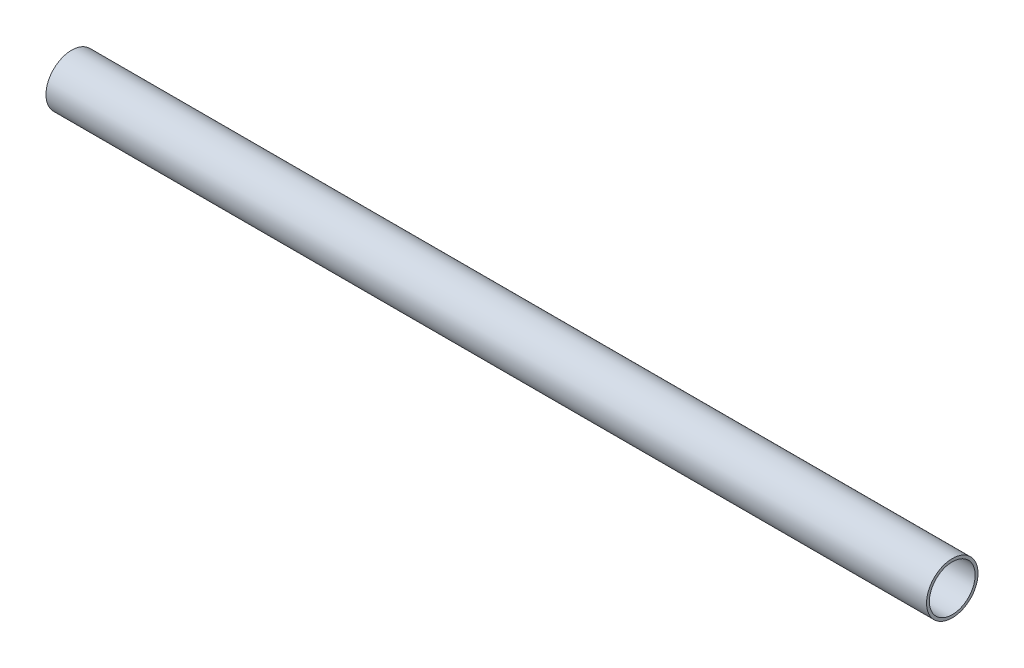
SolidWorks part; units mm, degrees
material "Rubber"
ref_plane "Front Plane" through (0, 0, 0) normal (0, 0, 1) x (1, 0, 0)
ref_plane "Top Plane" through (0, 0, 0) normal (0, 1, 0) x (1, 0, 0)
ref_plane "Right Plane" through (0, 0, 0) normal (1, 0, 0) x (0, 0, -1)
sketch "Sketch1" plane through (0, 0, 0) normal (0, 0, 1) x (1, 0, 0)
  line L0 (0, 14.2875) -> (0, 0)
  line L1 (0, 0) -> (31.75, 0)
  line L2 (31.75, 0) -> (31.75, 12.7)
  line L3 (31.75, 12.7) -> (488.95, 12.7)
  line L4 (488.95, 12.7) -> (488.95, 14.2875)
  line L5 (488.95, 14.2875) -> (0, 14.2875)
  line L6 (0, 0) -> (488.95, 0) construction
revolve "Revolve1" add sketch "Sketch1" angle 360 about L6
